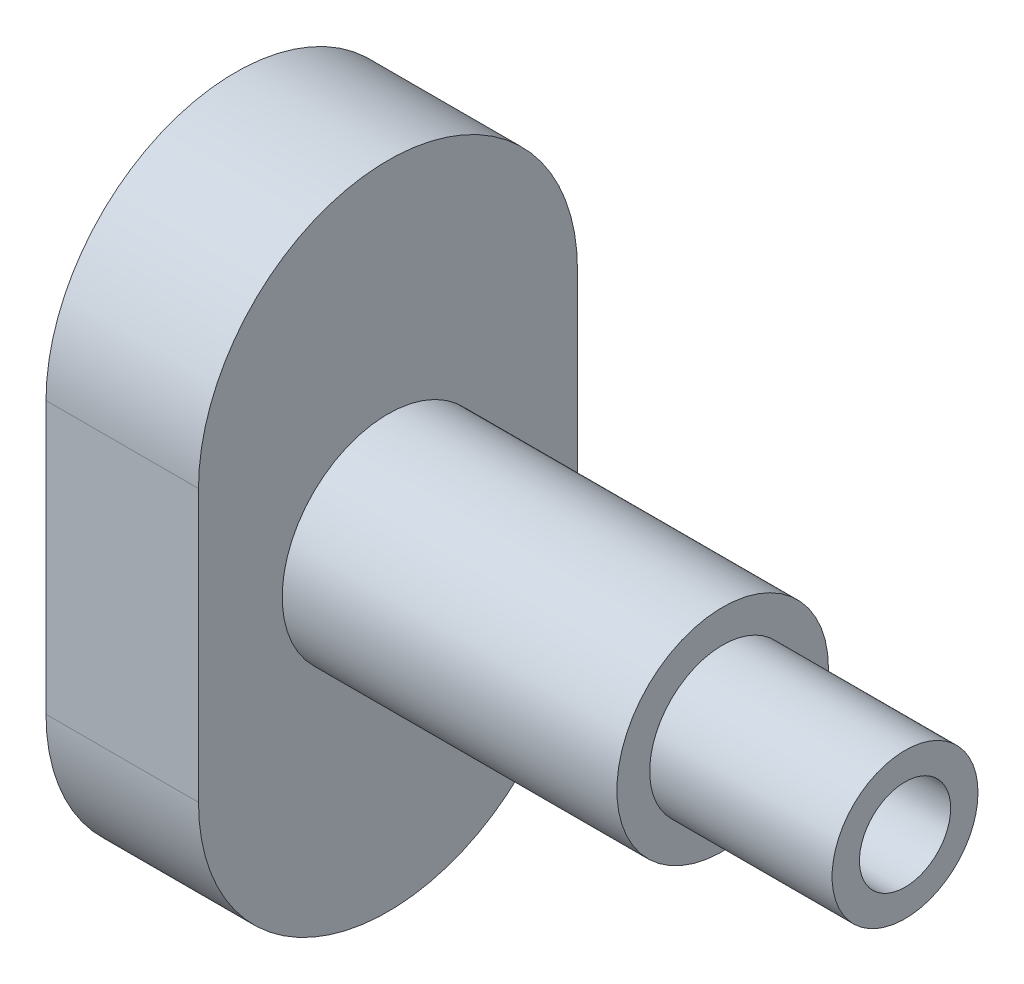
SolidWorks part; units mm, degrees
ref_plane "Front Plane" through (0, 0, 0) normal (1, 0, 0) x (0, 1, 0)
ref_plane "Top Plane" through (0, 0, 0) normal (0, 0, 1) x (0, 1, 0)
ref_plane "Right Plane" through (0, 0, 0) normal (0, 1, 0) x (-1, 0, 0)
sketch "Sketch1" plane through (0, 0, 0) normal (1, 0, 0) x (0, 1, 0)
  line L0 (-7.45, 0) -> (7.45, 0) construction
  line L1 (-7.45, 10.39) -> (7.45, 10.39)
  line L2 (-7.45, -10.39) -> (7.45, -10.39)
  arc A0 (-7.45, 10.39) -> (-7.45, -10.39) centre (-7.45, 0) ccw
  arc A1 (7.45, -10.39) -> (7.45, 10.39) centre (7.45, 0) ccw
  point P3 (0, 0)
  dimension "D2" = 14.9
  dimension "D1" = 20.78
extrude "Boss-Extrude1" add sketch "Sketch1" along normal blind 8.36
sketch "Sketch2" plane through (8.36, 0, 0) normal (1, 0, 0) x (0, 1, 0)
  circle A0 centre (0, 0) radius 5.8
  dimension "D1" = 11.6
extrude "Boss-Extrude2" add sketch "Sketch2" along normal blind 18.35
sketch "Sketch3" plane through (26.71, 0, 0) normal (1, 0, 0) x (0, 1, 0)
  circle A0 centre (0, 0) radius 4
  dimension "D1" = 8
extrude "Boss-Extrude3" add sketch "Sketch3" along normal blind 10
sketch "Sketch4" plane through (36.71, 0, 0) normal (1, 0, 0) x (0, 1, 0)
  circle A0 centre (0, 0) radius 2.5
  dimension "D1" = 5
extrude "Cut-Extrude1" cut sketch "Sketch4" against normal through all
